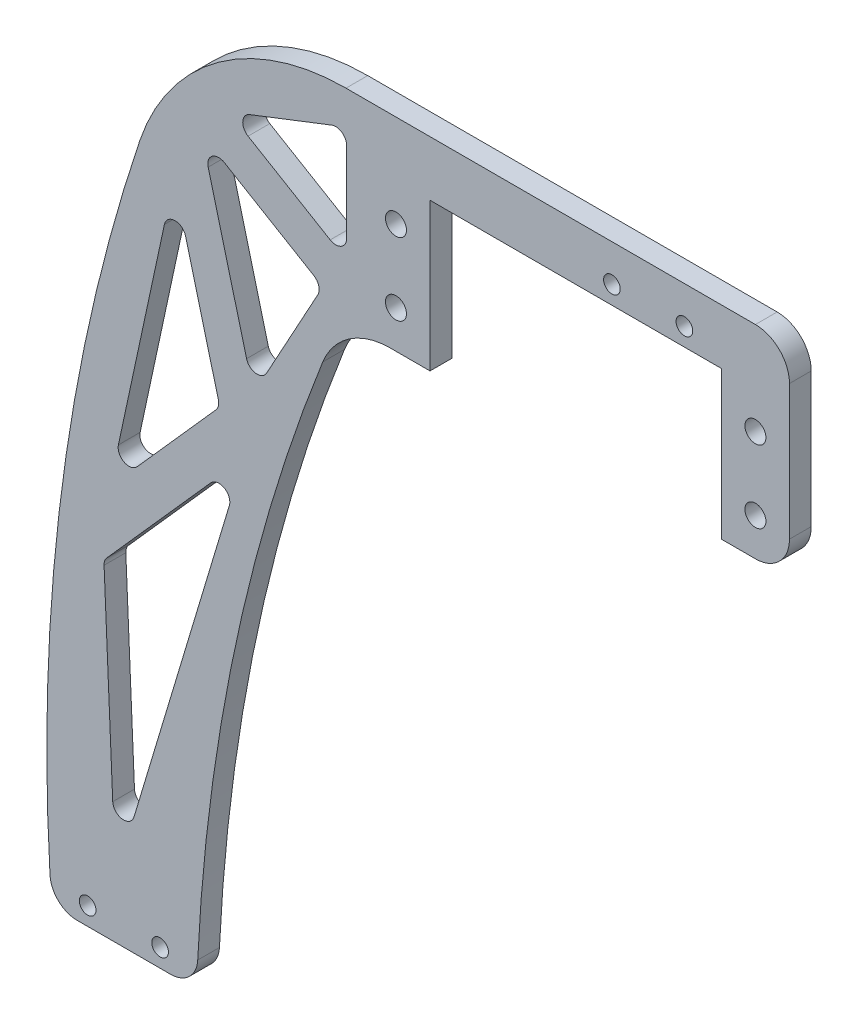
SolidWorks part; units mm, degrees
material "ABS"
ref_plane "Front" through (0, 0, 0) normal (0, 0, 1) x (1, 0, 0)
ref_plane "Top" through (0, 0, 0) normal (0, 1, 0) x (1, 0, 0)
ref_plane "Right" through (0, 0, 0) normal (1, 0, 0) x (0, 0, -1)
sketch "Esquisse1" plane through (0, 0, 0) normal (0, 0, 1) x (1, 0, 0)
  line L0 (-30.9, 14) -> (-50.9, 14)
  line L1 (-30.9, 14) -> (30.9, 14)
  line L3 (-30.9, -14) -> (30.9, -14)
  line L4 (30.9, 14) -> (30.9, -14)
  line L5 (-30.9, 14) -> (30.9, -14) construction
  line L6 (-30.9, -14) -> (30.9, 14) construction
  line L7 (-50.9, -104) -> (-70.9, -104) construction
  line L8 (-70.9, -104) -> (-50.9, -104)
  arc A3 (-30.9, -14) -> (-50.9, -104) centre (198.9621, -112.3027) ccw
  arc A5 (-50.9, 14) -> (-70.9, -104) centre (178.4192, -85.5626) ccw
  point P0 (0, 0)
  dimension "D1" = 250
  dimension "D4" = 250
  dimension "D7" = 20
  dimension "D2" = 61.8
  dimension "D3" = 28
extrude "Boss.-Extru.1" add sketch "Esquisse1" along normal blind 3
sketch "Esquisse2" plane through (0, 0, 3) normal (0, 0, 1) x (1, 0, 0)
  line L0 (-30.9, 12.9) -> (-30.9, -14) construction
  line L1 (30.9, -14) -> (30.9, 14) construction
  line L2 (-30.9, -14) -> (30.9, -14) construction
  line L3 (-18.7, -14) -> (21.5, -14)
  line L4 (-18.7, -14) -> (-18.7, 6.4)
  line L5 (-18.7, 6.4) -> (21.5, 6.4)
  line L6 (21.5, -14) -> (21.5, 6.4)
  line L7 (-30.9, -14) -> (30.9, -14) construction
  dimension "D1" = 40.2
  dimension "D2" = 12.2
  dimension "D3" = 20.4
  dimension "D4" = 9.4
extrude "Enlèv. mat.-Extru.1" cut sketch "Esquisse2" against normal up to next
sketch "Esquisse3" plane through (0, 0, 3) normal (0, 0, 1) x (1, 0, 0)
  line L0 (21.5, -14) -> (21.5, 6.4) construction
  line L2 (21.5, -14) -> (30.9, -14) construction
  circle A2 centre (26.2, -8.8) radius 1.45
  circle A4 centre (-23.4, -8.8) radius 1.45
  circle A5 centre (-23.4, 1.2) radius 1.45
  circle A6 centre (26.2, 1.2) radius 1.45
  dimension "D1" = 2.9
  dimension "D2" = 4.7
  dimension "D3" = 5.2
  dimension "D4" = 2
  dimension "D5" = 2
extrude "Enlèv. mat.-Extru.2" cut sketch "Esquisse3" against normal up to next
fillet "Congé2" radius 4.7 2 edges at (30.9, -14, 1.5) (30.9, 14, 1.5)
fillet "Congé3" radius 10 1 edges at (-30.9, -14, 1.5)
fillet "Congé4" radius 30 1 edges at (-50.9, 14, 1.5)
fillet "Congé5" radius 3.75 2 edges at (-50.9, -104, 1.5) (-70.9, -104, 1.5)
sketch "Esquisse4" plane through (0, 0, 3) normal (0, 0, 1) x (1, 0, 0)
  line L0 (-33.4844, -11.3585) -> (-43.0589, -28.8396)
  line L1 (-43.0589, -28.8396) -> (-50.2384, -1.4139)
  line L2 (-50.2384, -1.4139) -> (-33.4844, -11.3585)
  line L3 (-54.0258, -8.664) -> (-47.7047, -32.8105)
  line L4 (-47.7047, -32.8105) -> (-62.9006, -49.9135)
  line L5 (-62.9006, -49.9135) -> (-54.0258, -8.664)
  line L6 (-44.434, -37.41) -> (-63.7025, -59.0966)
  line L7 (-63.7025, -59.0966) -> (-62.0979, -96.2255)
  line L8 (-62.0979, -96.2255) -> (-44.434, -37.41)
  line L9 (-46.4573, 3.0782) -> (-30.2087, -6.5664)
  line L10 (-30.2087, -6.5664) -> (-30.2087, 9.3927)
  line L11 (-30.2087, 9.3927) -> (-46.4573, 3.0782)
  dimension "D1" = 5.5
  dimension "D2" = 5.5
extrude "Enlèv. mat.-Extru.3" cut sketch "Esquisse4" against normal up to next
fillet "Congé6" radius 1.5 12 edges at (-62.0979, -96.2255, 1.5) (-63.7025, -59.0966, 1.5) (-44.434, -37.41, 1.5) (-47.7047, -32.8105, 1.5) (-54.0258, -8.664, 1.5) (-62.9006, -49.9135, 1.5) (-43.0589, -28.8396, 1.5) (-33.4844, -11.3585, 1.5) (-50.2384, -1.4139, 1.5) (-30.2087, 9.3927, 1.5) (-30.2087, -6.5664, 1.5) (-46.4573, 3.0782, 1.5)
sketch "Esquisse5" plane through (0, 0, 3) normal (0, 0, 1) x (1, 0, 0)
  line L1 (21.5, 6.4) -> (-18.7, 6.4) construction
  line L2 (21.5, -14) -> (21.5, 6.4) construction
  circle A0 centre (16.4, 8.9) radius 1.15
  circle A1 centre (6.4, 8.9) radius 1.15
  dimension "D1" = 2.5
  dimension "D2" = 10
  dimension "D3" = 5.1
  dimension "D4" = 2.3
extrude "Enlèv. mat.-Extru.4" cut sketch "Esquisse5" against normal up to next
sketch "Esquisse6" plane through (0, 0, 3) normal (0, 0, 1) x (1, 0, 0)
  line L0 (-67.3924, -104) -> (-54.5015, -104) construction
  circle A0 centre (-65.9457, -101.5) radius 1.15
  circle A1 centre (-55.9457, -101.5) radius 1.15
  dimension "D1" = 2.3
  dimension "D2" = 2.5
  dimension "D3" = 5.19
  dimension "D4" = 2
extrude "Enlèv. mat.-Extru.5" cut sketch "Esquisse6" against normal blind 10
